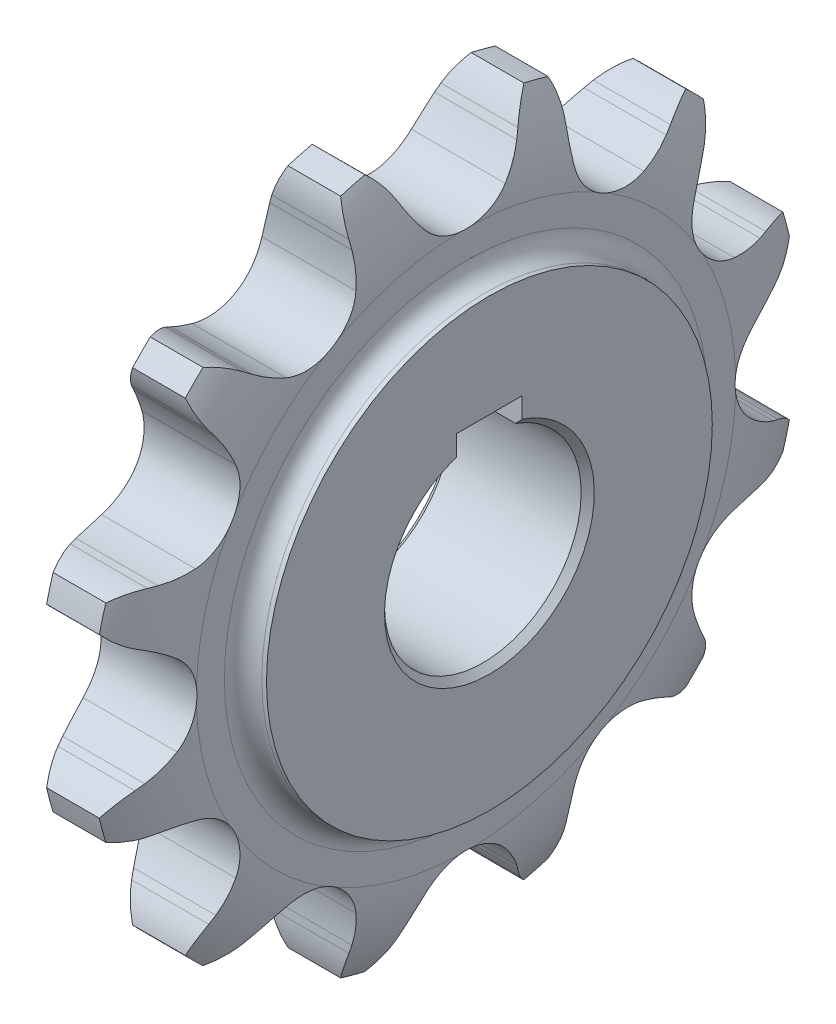
SolidWorks part; units mm, degrees
ref_plane "前视基准面" through (0, 0, 0) normal (0, 0, 1) x (1, 0, 0)
ref_plane "上视基准面" through (0, 0, 0) normal (0, 1, 0) x (1, 0, 0)
ref_plane "右视基准面" through (0, 0, 0) normal (1, 0, 0) x (0, 0, -1)
sketch "草图1" plane through (0, 0, 0) normal (0, 0, 1) x (1, 0, 0)
  line L0 (-12.7, 0) -> (12.7, 0) construction
  line L1 (-10.8883, 15) -> (-10.8883, 34)
  line L2 (-10.8883, 34) -> (-10.1754, 34)
  line L3 (-7.3238, 36.8516) -> (-7.3237, 41.129)
  line L4 (-4.0217, 54) -> (4.0217, 54)
  line L5 (7.3237, 41.129) -> (7.3238, 36.8516)
  line L6 (10.1754, 34) -> (10.8883, 34)
  line L7 (10.8883, 34) -> (10.8883, 15)
  line L8 (10.8883, 15) -> (-10.8883, 15)
  line L9 (0, 0) -> (0, 54) construction
  line L10 (-6.1635, 49.069) -> (6.1635, 49.069) construction
  line L11 (-6.1635, -49.069) -> (6.1635, -49.069) construction
  line L12 (12.7, 0) -> (24.7, 0) construction
  line L13 (-7.3237, 41.129) -> (3.7984, 41.129) construction
  line L14 (-7.3237, -41.129) -> (3.7984, -41.129) construction
  line L15 (24.7, 0) -> (40.58, 0) construction
  line L16 (40.58, 0) -> (64.71, 0) construction
  line L17 (64.71, 0) -> (80.46, 0) construction
  line L18 (80.46, 0) -> (109.75, 0) construction
  arc A0 (-4.0217, 54) -> (-7.3237, 41.129) centre (18.0739, 41.4724) ccw
  arc A1 (4.0217, 54) -> (7.3237, 41.129) centre (-18.0739, 41.4724) cw
  arc A2 (7.3238, 36.8516) -> (10.1754, 34) centre (10.1754, 36.8516) ccw
  arc A3 (-10.1754, 34) -> (-7.3238, 36.8516) centre (-10.1754, 36.8516) ccw
  point P30 (7.3237, 34)
  point P33 (-7.3237, 34)
  dimension "D1" = 7.129
  dimension "rx" = 25.4
  dimension "D3" = 2.8516
  dimension "d" = 98.1381
  dimension "p" = 25.4
  dimension "z" = 12
  dimension "da" = 108
  dimension "df" = 82.2581
  dimension "dr" = 15.88
  dimension "dk" = 30
  dimension "dg" = 68
  dimension "h" = 24.13
  dimension "bf1" = 14.6475
  dimension "b1" = 15.75
  dimension "ba" = 3.302
  dimension "D2" = 3.5645
  dimension "pt" = 29.29
revolve "旋转1" add sketch "草图1" angle 360 about L0
sketch "草图2" plane through (0, 0, 0) normal (1, 0, 0) x (0, 0, -1)
  line L0 (0, 0) -> (0, 54) construction
  line L1 (0, 0) -> (-13.9762, 52.16) construction
  line L2 (0, 0) -> (-27, 46.7654) construction
  line L3 (6.1511, 43.9076) -> (8.5213, 41.9188) construction
  line L4 (8.7965, 47.9297) -> (-9.7318, 57.235) construction
  line L5 (0, 0) -> (13.9762, 52.16) construction
  line L6 (8.7965, 47.9297) -> (9.3552, 49.0422)
  line L7 (-8.7965, 47.9297) -> (-9.3552, 49.0422)
  circle A0 centre (0, 0) radius 54 construction
  arc A1 (6.1511, 43.9076) -> (-6.1511, 43.9076) centre (0, 49.069) cw
  arc A2 (6.1511, 43.9076) -> (8.7965, 47.9297) centre (-9.7318, 57.235) ccw
  arc A3 (12.1196, 52.6224) -> (9.3552, 49.0422) centre (19.9406, 43.726) ccw
  arc A4 (-6.1511, 43.9076) -> (-8.7965, 47.9297) centre (9.7318, 57.235) cw
  arc A5 (-12.1196, 52.6224) -> (-9.3552, 49.0422) centre (-19.9406, 43.726) cw
  arc A7 (12.1196, 52.6224) -> (-12.1196, 52.6224) centre (0, 0) ccw
  dimension "r1" = 8.0297
  dimension "r3" = 11.8454
  dimension "D1" = 30
  dimension "D2" = 15
  dimension "α/2" = 50
  dimension "M" = 9.7318
  dimension "T" = 8.166
  dimension "β" = 13.333
  dimension "γ/2" = 11.667
  dimension "bc" = 1.2448
extrude "切除-拉伸1" cut sketch "草图2" against normal mid plane 21.7765
pattern_circular "阵列(圆周)1" count 12 over 360 about axis through (0, 0, 0) along (1, 0, 0) of "切除-拉伸1"
sketch "草图3" plane through (0, 0, 0) normal (0, 0, 1) x (1, 0, 0)
  line L0 (10.8883, 15) -> (9.1117, 15)
  line L3 (9.1117, 15) -> (9.1117, 28.8147)
  line L4 (9.1117, 28.8147) -> (10.8883, 28.8147)
  line L5 (10.8883, 28.8147) -> (10.8883, 15)
  line L6 (0, 0) -> (9.5, 0) construction
  line L8 (-10.8883, 34) -> (-10.8883, -34) construction
  dimension "h" = 13.8147
  dimension "K" = 9.5
  dimension "L" = 20
revolve "旋转2" add sketch "草图3" angle 360 about L6
sketch "草图4" plane through (-10.8883, 0, 0) normal (-1, 0, 0) x (0, 0, 1)
  line L1 (-5, 14.1421) -> (5, 14.1421)
  line L2 (-5, 14.1421) -> (-5, 18.3)
  line L3 (-5, 18.3) -> (5, 18.3)
  line L4 (5, 14.1421) -> (5, 18.3)
  circle A0 centre (0, 0) radius 15 construction
  point P6 (1, 18.3)
  dimension "D1" = 18.3
  dimension "键槽宽度" = 10
  dimension "t1" = 4
extrude "切除-拉伸2" cut sketch "草图4" against normal through all
chamfer "倒角1" distance 1 angle 45 1 edges at (-10.8883, -15, 0)
chamfer "倒角3" distance 1 angle 45 1 edges at (10.8883, -15, 0)
